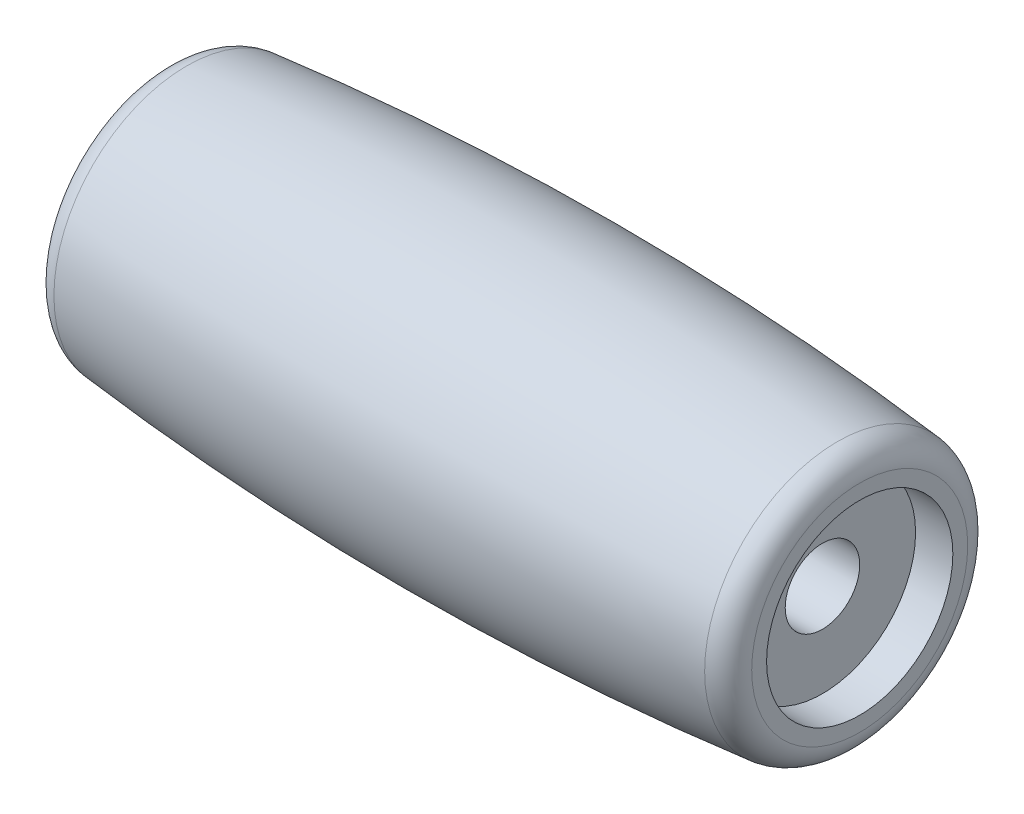
SolidWorks part; units mm, degrees
ref_plane "Front Plane" through (0, 0, 0) normal (0, 0, 1) x (1, 0, 0)
ref_plane "Top Plane" through (0, 0, 0) normal (0, 1, 0) x (1, 0, 0)
ref_plane "Right Plane" through (0, 0, 0) normal (1, 0, 0) x (0, 0, -1)
sketch "Sketch1" plane through (0, 0, 0) normal (0, 0, 1) x (1, 0, 0)
  line L0 (-14, 0) -> (14, 0) construction
  line L1 (-14, 3.75) -> (-14, 0)
  line L2 (0, 0) -> (0, 6) construction
  line L4 (-12.5, 1.5) -> (12.5, 1.5)
  line L5 (-14, 3.75) -> (-14, 4.3486)
  line L7 (14, 3.75) -> (14, 0)
  line L8 (14, 3.75) -> (14, 4.3486)
  line L9 (-14, 3.75) -> (-12.5, 3.75)
  line L10 (-12.5, 3.75) -> (-12.5, 1.5)
  line L11 (12.5, 3.75) -> (12.5, 1.5)
  line L12 (14, 3.75) -> (12.5, 3.75)
  arc A0 (-13.1, 5.3436) -> (13.1, 5.3436) centre (0, -125.0417) cw
  arc A1 (14, 4.3486) -> (13.1, 5.3436) centre (13, 4.3486) ccw
  arc A2 (-13.1, 5.3436) -> (-14, 4.3486) centre (-13, 4.3486) ccw
  point P3 (0, 0)
  point P12 (0, 1.5)
  point P18 (14, 5.25)
  point P21 (-14, 5.25)
  dimension "D7" = 1
  dimension "D1" = 6
  dimension "D2" = 14
  dimension "D3" = 3.75
  dimension "D4" = 1.5
  dimension "D5" = 1.5
  dimension "D6" = 1.5
revolve "Revolve1" add sketch "Sketch1" angle 360 about L0
